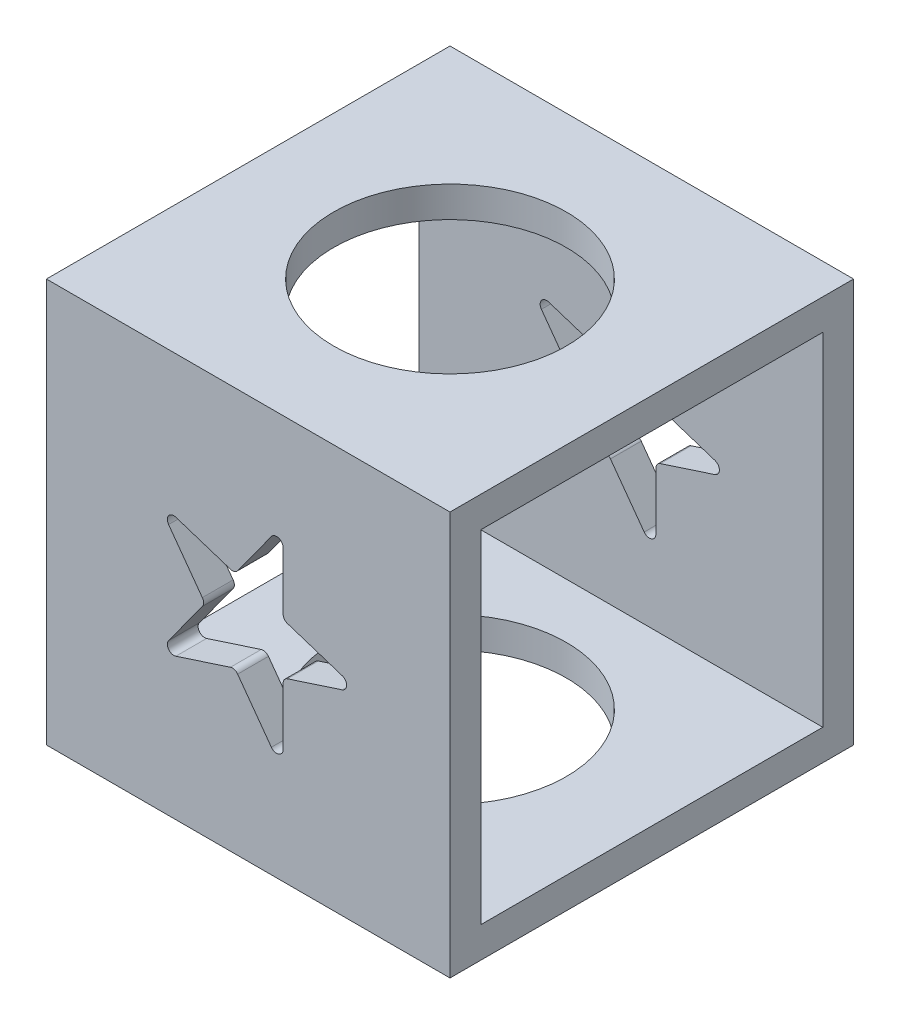
SolidWorks part; units mm, degrees
ref_plane "Front Plane" through (0, 0, 0) normal (0, 0, 1) x (1, 0, 0)
ref_plane "Top Plane" through (0, 0, 0) normal (0, 1, 0) x (1, 0, 0)
ref_plane "Right Plane" through (0, 0, 0) normal (1, 0, 0) x (0, 0, -1)
sketch "Sketch1" plane through (0, 0, 0) normal (0, 1, 0) x (1, 0, 0)
  line L1 (-46.8313, 46.8312) -> (46.8312, 46.8312)
  line L2 (-46.8313, 46.8312) -> (-46.8312, -46.8312)
  line L3 (-46.8312, -46.8312) -> (46.8313, -46.8312)
  line L4 (46.8312, 46.8312) -> (46.8313, -46.8312)
  line L5 (-46.8313, 46.8312) -> (46.8313, -46.8312) construction
  line L6 (-46.8312, -46.8312) -> (46.8312, 46.8312) construction
  point P0 (0, 0)
  dimension "D1" = 93.6625
  dimension "D2" = 93.6625
extrude "Boss-Extrude1" add sketch "Sketch1" along normal blind 93.6625
sketch "Sketch3" plane through (0, 93.6625, 0) normal (0, 1, 0) x (1, 0, 0)
  circle A0 centre (0, 0) radius 26.9875
extrude "Cut-Extrude1" cut sketch "Sketch3" against normal through all
sketch "Sketch4" plane through (-46.8312, 0, 0) normal (-1, 0, 0) x (0, 0, 1)
  line L1 (-39.6875, 86.5188) -> (39.6875, 86.5188)
  line L2 (-39.6875, 86.5188) -> (-39.6875, 7.1438)
  line L3 (-39.6875, 7.1438) -> (39.6875, 7.1438)
  line L4 (39.6875, 86.5188) -> (39.6875, 7.1438)
  line L5 (-39.6875, 86.5188) -> (39.6875, 7.1438) construction
  line L6 (-39.6875, 7.1438) -> (39.6875, 86.5188) construction
  line L11 (46.8312, 93.6625) -> (46.8312, 0) construction
  line L12 (46.8312, 46.8313) -> (-46.8313, 46.8313) construction
  line L13 (-46.8313, 93.6625) -> (-46.8313, 0) construction
  point P0 (0, 46.8313)
  point P5 (0, 46.8313)
  dimension "D1" = 79.375
  dimension "D2" = 79.375
extrude "Cut-Extrude2" cut sketch "Sketch4" against normal through all
sketch "Sketch5" plane through (0, 0, 46.8312) normal (0, 0, 1) x (1, 0, 0)
  line L0 (-46.8312, 46.8313) -> (46.8313, 46.8313) construction
  line L1 (-46.8312, 93.6625) -> (-46.8312, 0) construction
  line L2 (46.8313, 93.6625) -> (46.8313, 0) construction
  line L3 (0, 93.6625) -> (0, 0) construction
  line L4 (-46.8312, 93.6625) -> (46.8313, 93.6625) construction
  line L5 (26.1938, 46.8312) -> (8.0943, 52.7121)
  line L6 (-21.1912, 62.2275) -> (-10.0051, 46.8312)
  line L7 (8.0943, 21.9195) -> (8.0943, 40.9504)
  line L8 (8.0943, 71.743) -> (-3.0918, 56.3467)
  line L9 (-21.1912, 31.435) -> (-3.0918, 37.3158)
  line L10 (-3.0918, 56.3467) -> (-21.1912, 62.2275)
  line L11 (8.0943, 40.9504) -> (26.1938, 46.8312)
  line L12 (-3.0918, 37.3158) -> (8.0943, 21.9195)
  line L13 (-10.0051, 46.8312) -> (-21.1912, 31.435)
  line L14 (8.0943, 52.7121) -> (8.0943, 71.743)
  point P11 (26.1938, 46.8312)
  point P13 (0, 46.8313)
  point P15 (8.0943, 21.9195)
  point P16 (-21.1912, 31.435)
  point P17 (-21.1912, 62.2275)
  point P18 (8.0943, 71.743)
  point P19 (0, 46.8313)
  dimension "D1" = 26.1938
  dimension "D2" = 5
extrude "Cut-Extrude3" cut sketch "Sketch5" against normal through all
fillet "Fillet1" radius 1.5 10 edges at (-3.0918, 37.3158, 43.2594) (-21.1912, 31.435, 43.2594) (-10.0051, 46.8312, 43.2594) (-21.1912, 62.2275, 43.2594) (-3.0918, 56.3467, 43.2594) (8.0943, 71.743, 43.2594) (8.0943, 21.9195, 43.2594) (8.0943, 40.9504, 43.2594) (8.0943, 52.7121, 43.2594) (26.1937, 46.8312, 43.2594)
fillet "Fillet2" radius 1.5 10 edges at (26.1938, 46.8312, -43.2594) (8.0943, 40.9504, -43.2594) (8.0943, 21.9195, -43.2594) (-3.0918, 37.3158, -43.2594) (-21.1912, 31.435, -43.2594) (-10.0051, 46.8312, -43.2594) (-21.1912, 62.2275, -43.2594) (-3.0918, 56.3467, -43.2594) (8.0943, 52.7121, -43.2594) (8.0943, 71.743, -43.2594)
